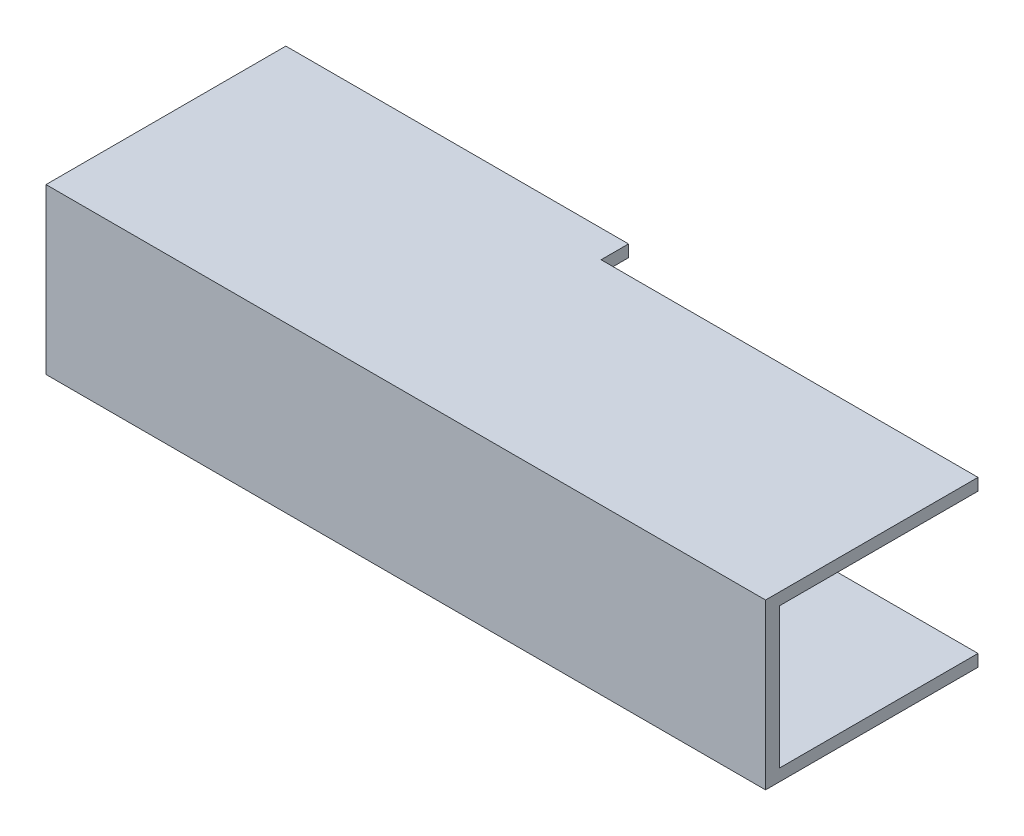
SolidWorks part; units mm, degrees
ref_plane "前视基准面" through (0, 0, 0) normal (0, 0, 1) x (1, 0, 0)
ref_plane "上视基准面" through (0, 0, 0) normal (0, 1, 0) x (1, 0, 0)
ref_plane "右视基准面" through (0, 0, 0) normal (1, 0, 0) x (0, 0, -1)
sketch "草图1" plane through (0, 0, 0) normal (0, 0, 1) x (1, 0, 0)
  line L1 (-68.5417, 18.0341) -> (36.4583, 18.0341)
  line L2 (-68.5417, 18.0341) -> (-68.5417, -5.9659)
  line L3 (-68.5417, -5.9659) -> (36.4583, -5.9659)
  line L4 (36.4583, 18.0341) -> (36.4583, -5.9659)
  dimension "D1" = 105
  dimension "D2" = 24
extrude "凸台-拉伸1" add sketch "草图1" along normal blind 35
sketch "草图2" plane through (-68.5417, 0, 0) normal (-1, 0, 0) x (0, 0, 1)
  line L0 (35, 18.0341) -> (35, -5.9659) construction
  line L1 (0, 18.0341) -> (0, -5.9659) construction
  line L2 (0, 16.2841) -> (33, 16.2841)
  line L3 (33, 16.2841) -> (33, -4.2159)
  line L4 (33, -4.2159) -> (0, -4.2159)
  line L5 (0, -4.2159) -> (0, 16.2841)
  line L6 (35, -5.9659) -> (0, -5.9659) construction
  line L7 (35, 18.0341) -> (0, 18.0341) construction
  dimension "D1" = 2
  dimension "D2" = 1.75
  dimension "D3" = 1.75
extrude "切除-拉伸1" cut sketch "草图2" against normal blind 50
sketch "草图3" plane through (36.4583, 0, 0) normal (1, 0, 0) x (0, 0, -1)
  line L0 (-33, 16.2841) -> (-4, 16.2841)
  line L1 (-4, 16.2841) -> (-4, 18.0341)
  line L2 (-35, 18.0341) -> (0, 18.0341) construction
  line L3 (-4, 18.0341) -> (0, 18.0341)
  line L4 (0, 18.0341) -> (0, -5.9659)
  line L5 (0, -5.9659) -> (-4, -5.9659)
  line L6 (-35, -5.9659) -> (0, -5.9659) construction
  line L7 (-4, -5.9659) -> (-4, -4.2159)
  line L8 (-4, -4.2159) -> (-33, -4.2159)
  line L9 (-33, -4.2159) -> (-33, 16.2841)
  line L10 (-35, -5.9659) -> (-35, 18.0341) construction
  dimension "D1" = 1.75
  dimension "D2" = 1.75
  dimension "D3" = 4
  dimension "D4" = 2
extrude "切除-拉伸2" cut sketch "草图3" against normal up to surface (55 mm away) up to face at (-18.5417, 6.0341, 16.5)
